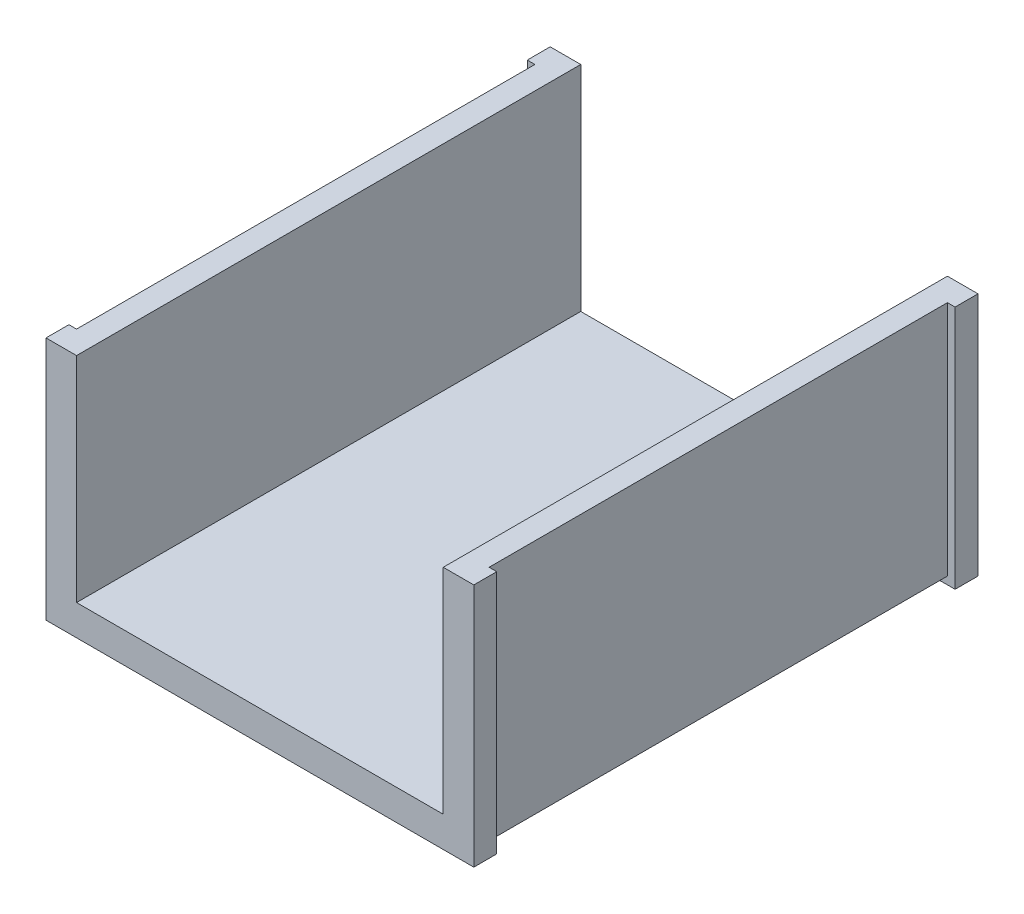
SolidWorks part; units mm, degrees
ref_plane "Front Plane" through (0, 0, 0) normal (0, 0, 1) x (1, 0, 0)
ref_plane "Top Plane" through (0, 0, 0) normal (0, 1, 0) x (1, 0, 0)
ref_plane "Right Plane" through (0, 0, 0) normal (1, 0, 0) x (0, 0, -1)
sketch "Sketch1" plane through (0, 0, 0) normal (0, 0, 1) x (1, 0, 0)
  line L1 (-37.75, -9.4775) -> (-65.75, -9.4775)
  line L2 (-37.75, -9.4775) -> (-37.75, -25.4775)
  line L3 (-37.75, -25.4775) -> (-65.75, -25.4775)
  line L4 (-65.75, -9.4775) -> (-65.75, -25.4775)
  line L5 (-63.75, -9.4775) -> (-39.75, -9.4775)
  line L6 (-63.75, -9.4775) -> (-63.75, -23.4775)
  line L7 (-63.75, -23.4775) -> (-39.75, -23.4775)
  line L8 (-39.75, -9.4775) -> (-39.75, -23.4775)
  dimension "D1" = 2
  dimension "D2" = 2
  dimension "D3" = 2
extrude "Boss-Extrude1" add sketch "Sketch1" against normal blind 33 contours L1 L8 L7 L6 L4 L3 L2
sketch "Sketch4" plane through (0, 0, 0) normal (0, 0, 1) x (1, 0, 0)
  line L0 (-63.75, -9.4775) -> (-65.75, -9.4775) construction
  line L1 (-65.25, -9.4775) -> (-38.25, -9.4775)
  line L2 (-65.25, -9.4775) -> (-65.25, -24.9775)
  line L3 (-65.25, -24.9775) -> (-38.25, -24.9775)
  line L4 (-38.25, -9.4775) -> (-38.25, -24.9775)
  line L5 (-65.75, -9.4775) -> (-65.75, -25.4775) construction
  line L6 (-37.75, -25.4775) -> (-65.75, -25.4775) construction
  line L7 (-37.75, -9.4775) -> (-37.75, -25.4775) construction
  line L9 (-65.75, -9.4775) -> (-37.75, -9.4775)
  line L10 (-65.75, -9.4775) -> (-65.75, -25.4775)
  line L11 (-65.75, -25.4775) -> (-37.75, -25.4775)
  line L12 (-37.75, -9.4775) -> (-37.75, -25.4775)
  line M9 (-37.75, -9.4775) -> (-39.75, -9.4775)
  line M13 (-63.75, -9.4775) -> (-65.75, -9.4775)
  line M14 (-65.75, -9.4775) -> (-65.75, -25.4775)
  line M15 (-65.75, -25.4775) -> (-37.75, -25.4775)
  line M16 (-37.75, -25.4775) -> (-37.75, -9.4775)
  dimension "D1" = 0.5
  dimension "D2" = 0.5
  dimension "D3" = 0.5
extrude "Cut-Extrude1" cut sketch "Sketch4" against normal blind 30 from offset 1.5 contours L4 L3 L2 M9 M13 M14 M15 M16
